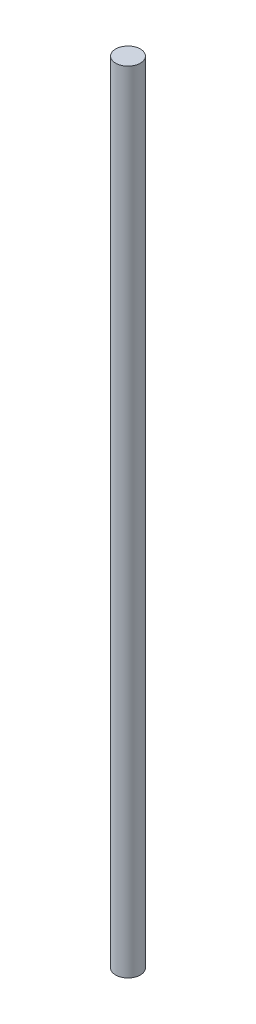
SolidWorks part; units mm, degrees
material "1060 合金"
ref_plane "前视基准面" through (0, 0, 0) normal (0, 0, 1) x (1, 0, 0)
ref_plane "上视基准面" through (0, 0, 0) normal (0, 1, 0) x (1, 0, 0)
ref_plane "右视基准面" through (0, 0, 0) normal (1, 0, 0) x (0, 0, -1)
other "Configuration Table"
sketch "草图1" plane through (0, 0, 0) normal (0, 1, 0) x (1, 0, 0)
  circle A0 centre (0, 0) radius 1
  dimension "D1" = 2
extrude "凸台-拉伸1" add sketch "草图1" along normal blind 64
